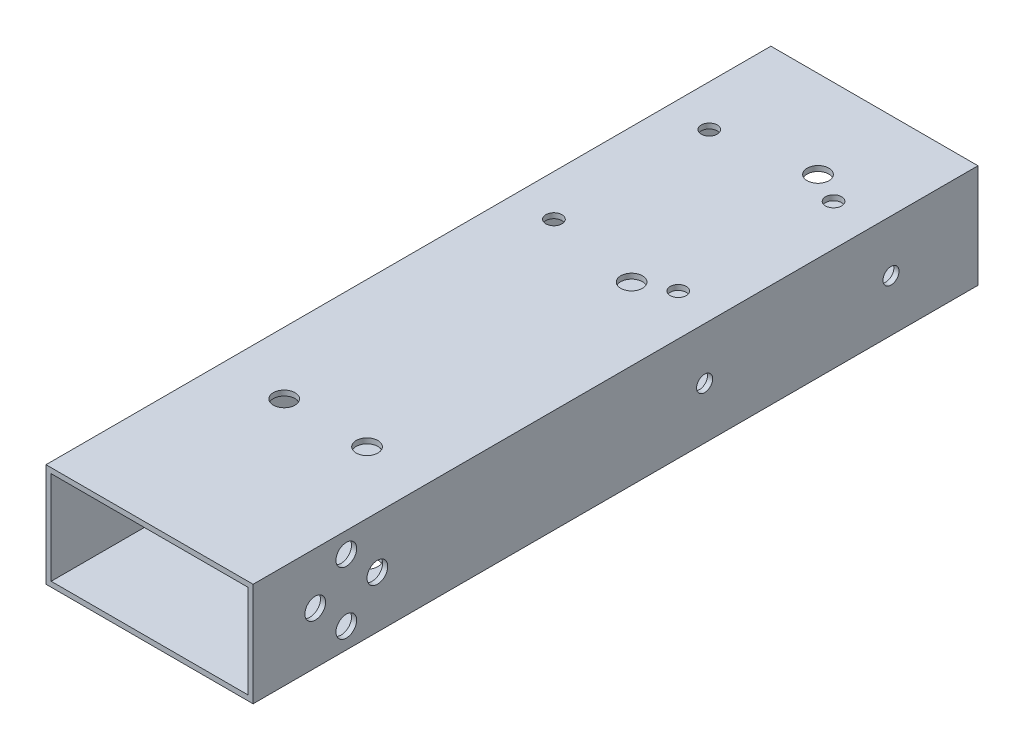
SolidWorks part; units mm, degrees
material "AISI 1015 钢，冷拔 (SS)"
ref_plane "前视基准面" through (0, 0, 0) normal (0, 0, 1) x (1, 0, 0)
ref_plane "上视基准面" through (0, 0, 0) normal (0, 1, 0) x (1, 0, 0)
ref_plane "右视基准面" through (0, 0, 0) normal (1, 0, 0) x (0, 0, -1)
other "Configuration Table"
sketch "草图1" plane through (0, 0, 0) normal (0, 0, 1) x (1, 0, 0)
  line L1 (0, 0) -> (40, 0)
  line L2 (0, 0) -> (0, 20)
  line L3 (0, 20) -> (40, 20)
  line L4 (40, 0) -> (40, 20)
  line L5 (1, 1) -> (39, 1)
  line L6 (1, 1) -> (1, 19)
  line L7 (1, 19) -> (39, 19)
  line L8 (39, 1) -> (39, 19)
  dimension "D1" = 40
  dimension "D2" = 20
  dimension "D3" = 1
  dimension "D4" = 1
  dimension "D5" = 1
  dimension "D6" = 1
extrude "凸台-拉伸1" add sketch "草图1" along normal blind 140
sketch "草图2" plane through (0, 0, 0) normal (1, 0, 0) x (0, 0, -1)
  line L0 (-70, 83.174) -> (-70, -57.7734) construction
  line L1 (-140, 20) -> (0, 20) construction
  line L2 (-234.5233, 10) -> (4.3455, 10) construction
  line L3 (0, 0) -> (0, 20) construction
  line L4 (-140, 0) -> (-140, 20) construction
  line L5 (-34.8, 83.174) -> (-34.8, -43.3259) construction
  line L6 (-122, 27.8475) -> (-122, -7.5542) construction
  circle A0 centre (-116, 10) radius 2
  circle A1 centre (-128, 10) radius 2
  circle A2 centre (-16.8, 10) radius 1.55
  circle A3 centre (-52.8, 10) radius 1.55
  circle A4 centre (-122, 16) radius 2
  circle A5 centre (-122, 4) radius 2
  point P2 (-70, 20)
  point P7 (0, 10)
  dimension "D1" = 4
  dimension "D5" = 3.1
  dimension "D2" = 12
  dimension "D3" = 12
  dimension "D4" = 34.8
  dimension "D6" = 36
  dimension "D7" = 6
  dimension "D8" = 12
extrude "切除-拉伸1" cut sketch "草图2" along normal through all
sketch "草图3" plane through (0, 0, 0) normal (0, 1, 0) x (1, 0, 0)
  line L0 (20, 7.4176) -> (20, -220.6816) construction
  line L1 (-71.6968, -34.9) -> (105.9098, -34.9) construction
  line L2 (40, -140) -> (40, 0) construction
  circle A0 centre (8, -19.9) radius 1.55
  circle A1 centre (32, -19.9) radius 1.55
  circle A2 centre (32, -49.9) radius 1.55
  circle A3 centre (8, -49.9) radius 1.55
  circle A4 centre (26, -16.9) radius 2.1
  circle A5 centre (26, -52.9) radius 2.1
  dimension "D1" = 3.1
  dimension "D6" = 4.2
  dimension "D2" = 20
  dimension "D3" = 24
  dimension "D4" = 19.9
  dimension "D5" = 30
  dimension "D7" = 36
  dimension "D8" = 14
extrude "切除-拉伸2" cut sketch "草图3" along normal through all
sketch "草图4" plane through (0, 20, 0) normal (0, 1, 0) x (1, 0, 0)
  line L0 (0, -140) -> (0, 0) construction
  line L1 (40, -140) -> (40, 0) construction
  line L2 (40, -140) -> (0, -140) construction
  circle A0 centre (28, -106) radius 2.1
  circle A1 centre (12, -106) radius 2.1
  dimension "D3" = 4.2
  dimension "D1" = 12
  dimension "D2" = 12
  dimension "D4" = 34
  dimension "D5" = 34
extrude "切除-拉伸3" cut sketch "草图4" against normal through all
